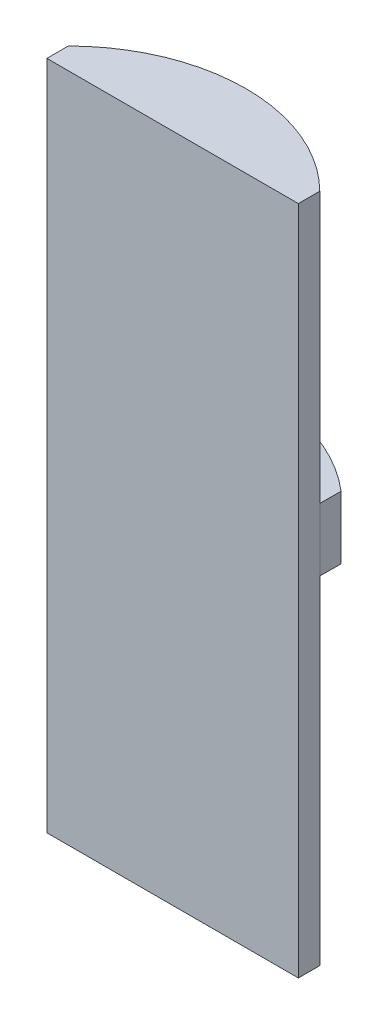
SolidWorks part; units mm, degrees
ref_plane "Front Plane" through (0, 0, 0) normal (0, 0, 1) x (1, 0, 0)
ref_plane "Top Plane" through (0, 0, 0) normal (0, 1, 0) x (1, 0, 0)
ref_plane "Right Plane" through (0, 0, 0) normal (1, 0, 0) x (0, 0, -1)
sketch "Sketch2" plane through (0, 0, 0) normal (0, 1, 0) x (1, 0, 0)
  line L0 (0, 0) -> (6, 0) construction
  line L1 (0, 0) -> (-6, 0) construction
  line L2 (0, 0) -> (0, 4.6967) construction
  line L3 (-6, 5) -> (-6, 6.0208) construction
  line L4 (-6, 6.0208) -> (-6, 5.0208) construction
  line L5 (-6, 0) -> (-6, 5) construction
  line L6 (6, 5) -> (6, 6.0208) construction
  line L7 (-6, 5) -> (-5.9214, 5)
  line L8 (5.9214, 5) -> (6, 5)
  line L9 (-6, 6.0208) -> (-6, 4.9054)
  line L10 (6, 5) -> (6, 6.0208)
  arc A0 (6, 6.0208) -> (-6, 6.0208) centre (0, 0) ccw
  circle A1 centre (0, 0) radius 7.8102 construction
  arc A3 (5.9214, 5) -> (-6, 4.9054) centre (0, 0) ccw
  dimension "D1" = 17
  dimension "D6" = 15.5
  dimension "D2" = 6
  dimension "D3" = 6
  dimension "D4" = 5
  dimension "D5" = 1
extrude "Boss-Extrude1" add sketch "Sketch2" along normal blind 29 contours A3 L8 A0 L7
ref_plane "Plane1" through (0, 10, 0) normal (0, -1, 0) x (-1, 0, 0)
sketch "Sketch3" plane through (0, 10, 0) normal (0, -1, 0) x (-1, 0, 0)
  line L0 (-7.75, 0) -> (-7.75, -3.4911)
  line L1 (7.75, 0) -> (7.75, -3.4911)
  arc A0 (7.75, -3.4911) -> (-7.75, -3.4911) centre (0, 0) ccw
  arc A1 (7.75, 0) -> (-7.75, 0) centre (0, 0) ccw
ref_plane "Plane2" through (0, 21.1, 0) normal (0, 1, 0) x (1, 0, 0)
sketch "Sketch4" plane through (0, 21.1, 0) normal (0, 1, 0) x (1, 0, 0)
  line L0 (6, 6.0208) -> (6.0068, 7.0343)
  line L1 (-6, 6.0208) -> (-6, 7.0401)
  arc A0 (6, 6.0208) -> (-6, 6.0208) centre (0, 0) ccw
  arc A1 (6.0068, 7.0343) -> (-6, 7.0401) centre (0, 0) ccw
  dimension "D1" = 18.5
extrude "Boss-Extrude3" add sketch "Sketch4" against normal blind 3
sketch "Sketch5" plane through (0, 0, 0) normal (0, -1, 0) x (1, 0, 0)
  line L0 (-5.9214, -5) -> (5.9214, -5)
  line L1 (-6, -6.0208) -> (6, -6.0208) construction
  arc A0 (-5.9214, -5) -> (5.9214, -5) centre (0, 0) ccw
  arc A1 (-5.9214, -5) -> (5.9214, -5) centre (0, 0) ccw construction
extrude "Boss-Extrude4" add sketch "Sketch5" against normal up to surface (29 mm away) up to face at (0, 29, -6.2118)
sketch "Sketch6" plane through (0, 0, 0) normal (0, -1, 0) x (1, 0, 0)
  line L5 (-8.5619, -1.309) -> (7.0339, -1.309)
  line L6 (-8.5619, -1.309) -> (-8.5619, -11.1818)
  line L7 (-8.5619, -11.1818) -> (7.0339, -11.1818)
  line L8 (7.0339, -1.309) -> (7.0339, -11.1818)
extrude "Cut-Extrude1" cut sketch "Sketch6" against normal blind 2
sketch "Sketch7" plane through (0, 29, 0) normal (0, 1, 0) x (1, 0, 0)
  line L0 (-6, 5) -> (6, 5)
  line L1 (6, 5) -> (6, 6.0208)
  line L2 (-6, 5) -> (-6, 6.0208)
  arc A1 (-6, 6.0208) -> (6, 6.0208) centre (0, 0) cw
extrude "Boss-Extrude5" add sketch "Sketch7" along normal blind 5
